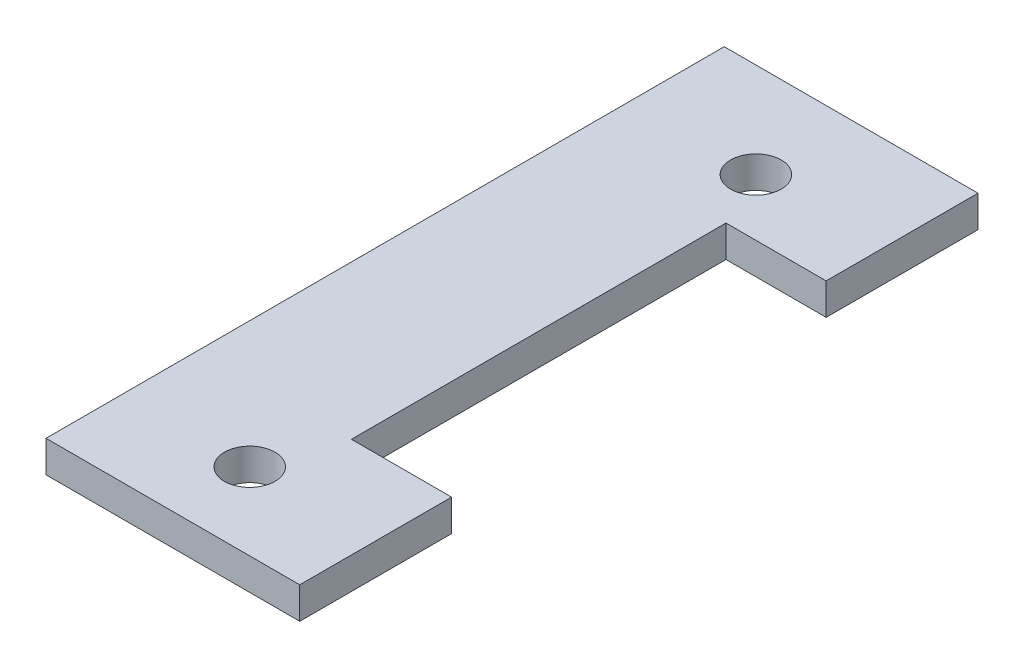
SolidWorks part; units mm, degrees
ref_plane "Front Plane" through (0, 0, 0) normal (0, 0, 1) x (1, 0, 0)
ref_plane "Top Plane" through (0, 0, 0) normal (0, 1, 0) x (1, 0, 0)
ref_plane "Right Plane" through (0, 0, 0) normal (1, 0, 0) x (0, 0, -1)
sketch "Sketch1" plane through (0, 0, 0) normal (0, 1, 0) x (1, 0, 0)
  line L0 (4.4887, -20.0648) -> (29.9555, -20.0648)
  line L1 (29.9555, -20.0648) -> (29.9555, -35.3048)
  line L2 (29.9555, -35.3048) -> (19.9029, -35.3048)
  line L3 (19.9029, -35.3048) -> (19.9029, -72.8968)
  line L4 (19.9029, -72.8968) -> (29.9555, -72.8968)
  line L5 (29.9555, -72.8968) -> (29.9555, -88.1368)
  line L6 (29.9555, -88.1368) -> (4.4887, -88.1368)
  line L7 (4.4887, -88.1368) -> (4.4887, -20.0648)
  point P8 (0, 0)
  point P9 (4.3728, -87.4718)
  point P11 (4.4887, -86.8175)
extrude "Boss-Extrude3" add sketch "Sketch1" along normal blind 3.175
sketch "Sketch13" plane through (0, 3.175, 0) normal (0, 1, 0) x (1, 0, 0)
  line L0 (4.4887, -20.0648) -> (4.4887, -88.1368) construction
  line L1 (29.9555, -20.0648) -> (4.4887, -20.0648) construction
  circle A0 centre (17.1887, -29.5898) radius 2.54
  circle A1 centre (17.1887, -80.3898) radius 2.54
  dimension "D1" = 5.08
  dimension "D2" = 5.08
  dimension "D3" = 12.7
  dimension "D4" = 12.7
  dimension "D5" = 9.525
  dimension "D6" = 50.8
extrude "Cut-Extrude1" cut sketch "Sketch13" against normal through all
